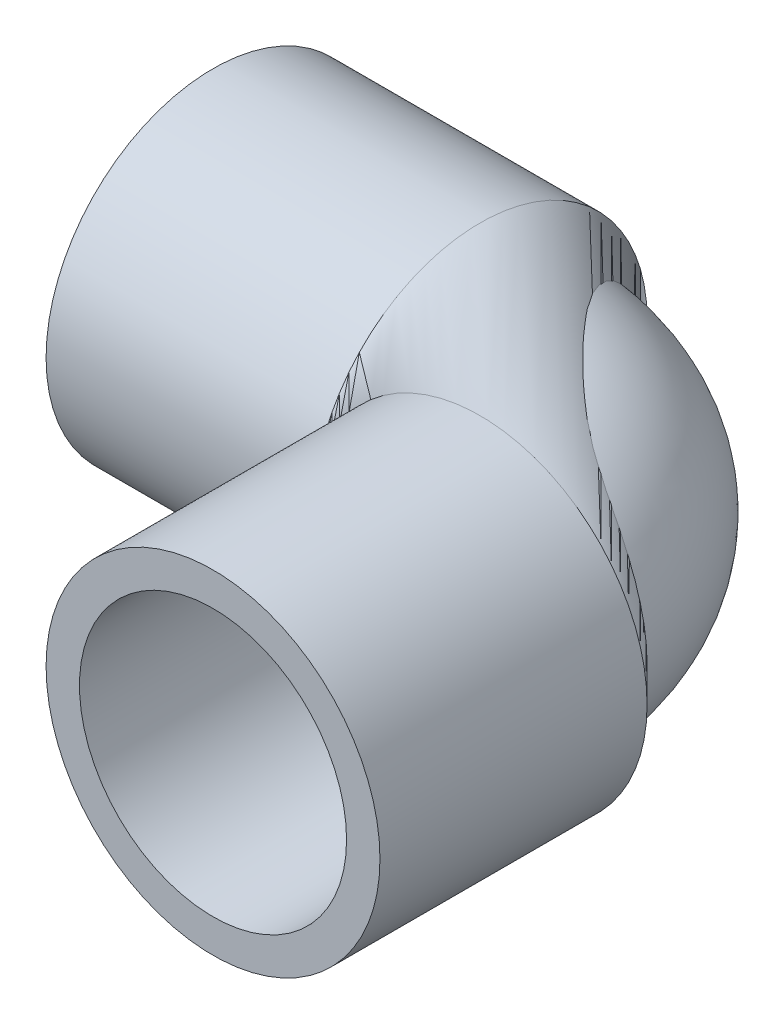
SolidWorks part; units mm, degrees
ref_plane "Front Plane" through (0, 0, 0) normal (0, 0, 1) x (1, 0, 0)
ref_plane "Top Plane" through (0, 0, 0) normal (0, 1, 0) x (1, 0, 0)
ref_plane "Right Plane" through (0, 0, 0) normal (1, 0, 0) x (0, 0, -1)
sketch "Sketch1" plane through (0, 0, 0) normal (0, 0, 1) x (1, 0, 0)
  line L0 (15.875, 0) -> (15.875, 29.5034)
  circle A0 centre (0, 0) radius 12.7
  circle A1 centre (0, 0) radius 15.875
  dimension "D1" = 25.4
  dimension "D2" = 31.75
extrude "Boss-Extrude1" add sketch "Sketch1" along normal blind 25.4 contours A1 A0
sketch "Sketch4" plane through (0, 0, 0) normal (0, 0, -1) x (-1, 0, 0)
  line L0 (15.875, 0) -> (15.875, 19.5559) construction
  circle A0 centre (0, 0) radius 15.875
  circle A1 centre (0, 0) radius 12.7
surface "Surface-Revolve2" sketch "Sketch4" parameters "D1"=90
surface "Surface-Fill1"
surface "Surface-Fill2"
sketch "Sketch5" plane through (-15.875, 0, 0) normal (1, 0, 0) x (0, 0, -1)
  circle A0 centre (15.875, 0) radius 12.7
  circle A1 centre (15.875, 0) radius 15.875
extrude "Boss-Extrude2" add sketch "Sketch5" against normal blind 25.4 separate body
